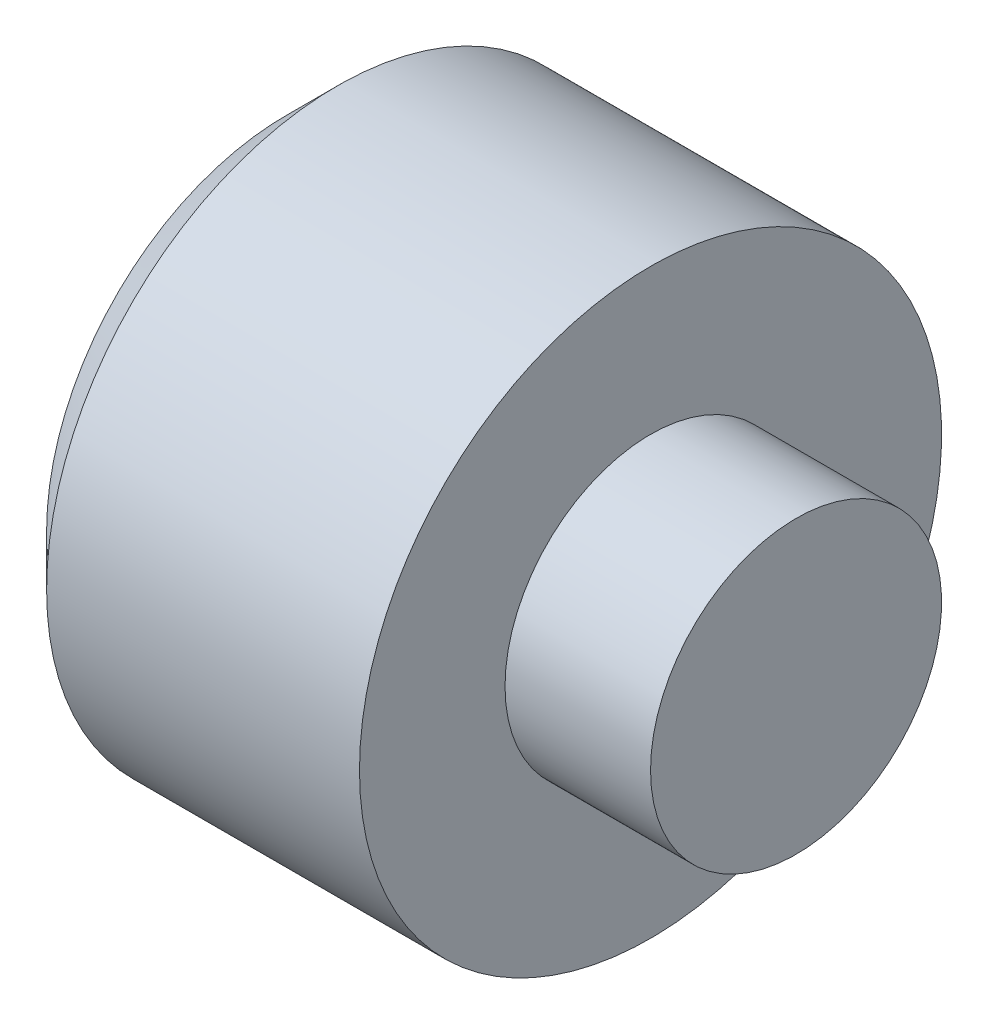
SolidWorks part; units mm, degrees
ref_plane "Plan1" through (0, 0, 0) normal (0, 0, 1) x (1, 0, 0)
ref_plane "Plan2" through (0, 0, 0) normal (0, 1, 0) x (1, 0, 0)
ref_plane "Plan3" through (0, 0, 0) normal (1, 0, 0) x (0, 0, -1)
sketch "Esquisse1" plane through (0, 0, 0) normal (0, 0, 1) x (1, 0, 0)
  line L0 (0, 0) -> (0, 4)
  line L1 (0, 4) -> (5, 4)
  line L2 (5, 4) -> (5, 2)
  line L3 (5, 2) -> (7, 2)
  line L4 (7, 2) -> (7, 0)
  line L5 (-2, 0) -> (10, 0) construction
  line L6 (0, 0) -> (7, 0)
  dimension "D1" = 4
  dimension "D2" = 5
revolve "Base-Révolution" add sketch "Esquisse1" angle 360 about L5
chamfer "Chanfrein1" distance 0.7 angle 45
